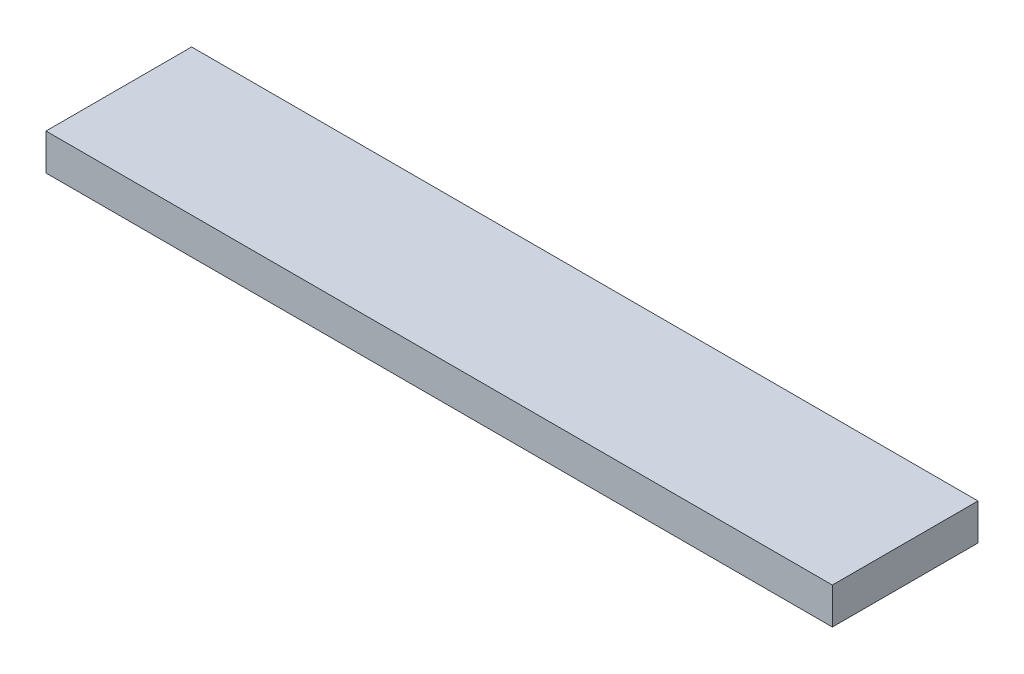
SolidWorks part; units mm, degrees
ref_plane "Front Plane" through (0, 0, 0) normal (0, 0, 1) x (1, 0, 0)
ref_plane "Top Plane" through (0, 0, 0) normal (0, 1, 0) x (1, 0, 0)
ref_plane "Right Plane" through (0, 0, 0) normal (1, 0, 0) x (0, 0, -1)
sketch "Sketch1" plane through (0, 0, 0) normal (0, 1, 0) x (1, 0, 0)
  line L1 (0, 0) -> (68.58, 0)
  line L2 (0, 0) -> (0, 12.7)
  line L3 (0, 12.7) -> (68.58, 12.7)
  line L4 (68.58, 0) -> (68.58, 12.7)
  dimension "D1" = 12.7
  dimension "D2" = 68.58
extrude "Boss-Extrude1" add sketch "Sketch1" along normal blind 3.175
